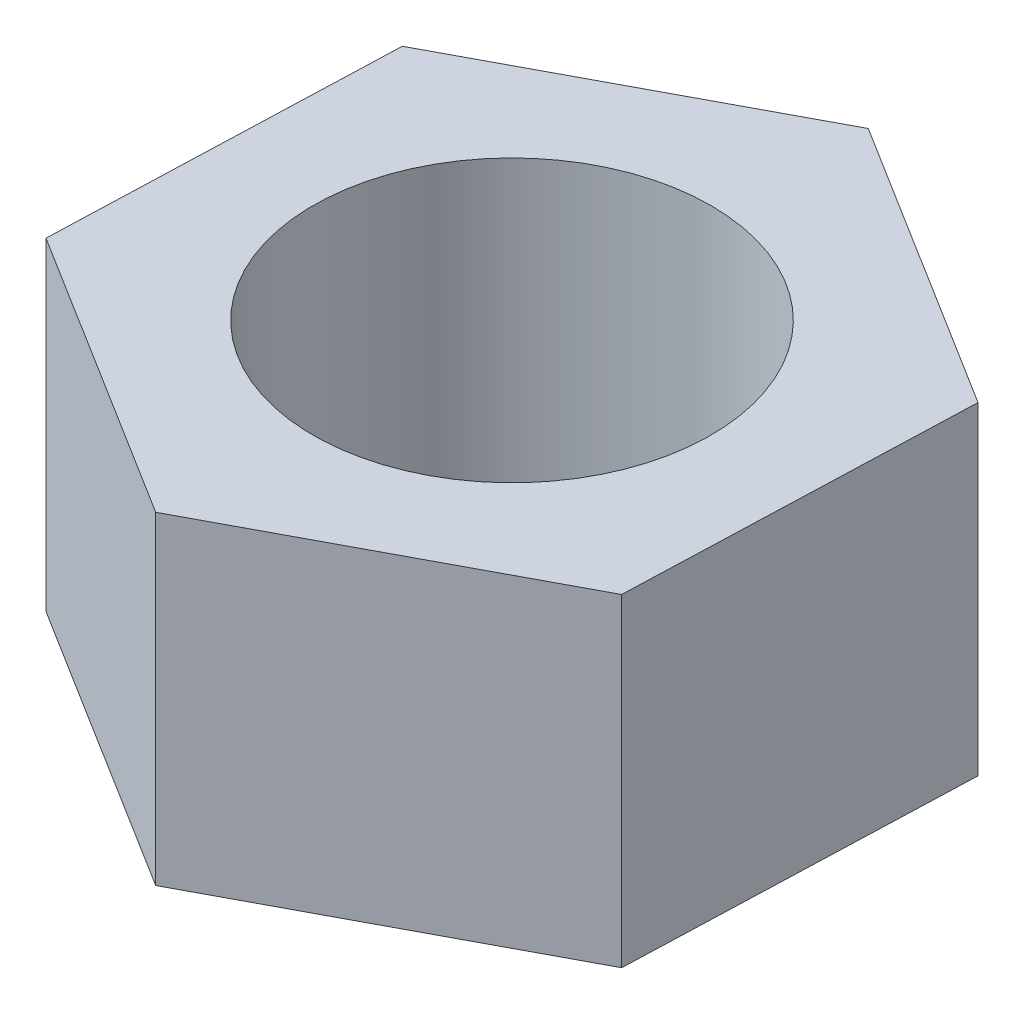
SolidWorks part; units mm, degrees
ref_plane "Front Plane" through (0, 0, 0) normal (0, 0, 1) x (1, 0, 0)
ref_plane "Top Plane" through (0, 0, 0) normal (0, 1, 0) x (1, 0, 0)
ref_plane "Right Plane" through (0, 0, 0) normal (1, 0, 0) x (0, 0, -1)
sketch "Sketch1" plane through (0, 0, 0) normal (0, 1, 0) x (1, 0, 0)
  line L1 (12.2336, 6.5068) -> (0.4817, 13.848)
  line L2 (0.4817, 13.848) -> (-11.7519, 7.3412)
  line L3 (-11.7519, 7.3412) -> (-12.2336, -6.5068)
  line L4 (-12.2336, -6.5068) -> (-0.4817, -13.848)
  line L5 (-0.4817, -13.848) -> (11.7519, -7.3412)
  line L6 (11.7519, -7.3412) -> (12.2336, 6.5068)
  circle A0 centre (0, 0) radius 12 construction
  circle A1 centre (0, 0) radius 8
  dimension "D1" = 24
  dimension "D2" = 16
extrude "Boss-Extrude1" add sketch "Sketch1" along normal blind 13
